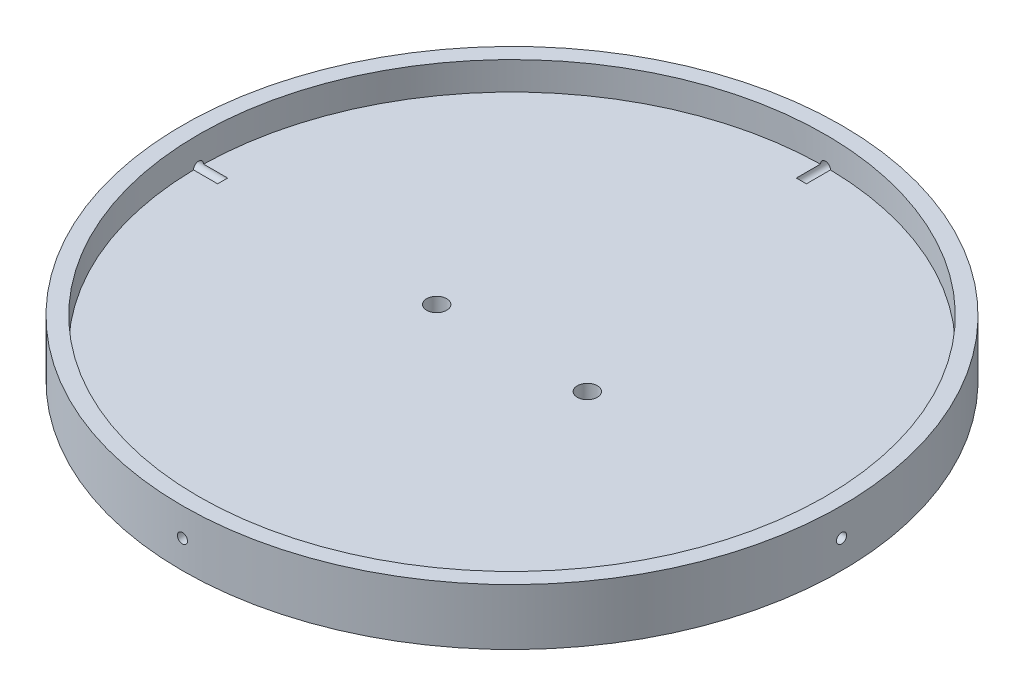
SolidWorks part; units mm, degrees
ref_plane "Front Plane" through (0, 0, 0) normal (0, 0, 1) x (1, 0, 0)
ref_plane "Top Plane" through (0, 0, 0) normal (0, 1, 0) x (1, 0, 0)
ref_plane "Right Plane" through (0, 0, 0) normal (1, 0, 0) x (0, 0, -1)
sketch "Sketch1" plane through (0, 0, 0) normal (0, 1, 0) x (1, 0, 0)
  line L0 (-82, 0) -> (82, 0) construction
  line L1 (0, 82) -> (0, -82) construction
  circle A0 centre (0, 0) radius 82
  dimension "D1" = 164
extrude "Boss-Extrude1" add sketch "Sketch1" along normal blind 7
sketch "Sketch2" plane through (0, 7, 0) normal (0, 1, 0) x (1, 0, 0)
  line L0 (-82, 0) -> (82, 0) construction
  circle A0 centre (-18.75, 0) radius 2.5
  circle A1 centre (18.75, 0) radius 2.5
  dimension "D1" = 5
  dimension "D2" = 5
  dimension "D3" = 18.75
  dimension "D4" = 18.75
extrude "Cut-Extrude1" cut sketch "Sketch2" against normal blind 10
sketch "Sketch3" plane through (0, 7, 0) normal (0, 1, 0) x (1, 0, 0)
  circle A0 centre (0, 0) radius 82
  circle A1 centre (0, 0) radius 78
  dimension "D1" = 164
  dimension "D2" = 156
extrude "Boss-Extrude2" add sketch "Sketch3" along normal blind 7
ref_plane "Plane1" through (82, 0, 0) normal (1, 0, 0) x (0, 0, -1)
sketch "Sketch4" plane through (82, 0, 0) normal (1, 0, 0) x (0, 0, -1)
  circle A0 centre (0, 7) radius 1.25
  dimension "D1" = 2.5
  dimension "D2" = 7
extrude "Cut-Extrude3" cut sketch "Sketch4" against normal blind 10
pattern_circular "CirPattern1" count 4 every 90 about axis through (0, 0, 0) along (0, 1, 0) of "Cut-Extrude3"
sketch "Sketch5" plane through (0, 0, 0) normal (0, 0, 1) x (1, 0, 0)
  circle A0 centre (0, 7) radius 1.25
  dimension "D1" = 2.5
sketch "Sketch6" plane through (0, 0, 0) normal (1, 0, 0) x (0, 0, -1)
  line L0 (0, 8.25) -> (0, 5.75) construction
  circle A0 centre (0, 7) radius 1.25
